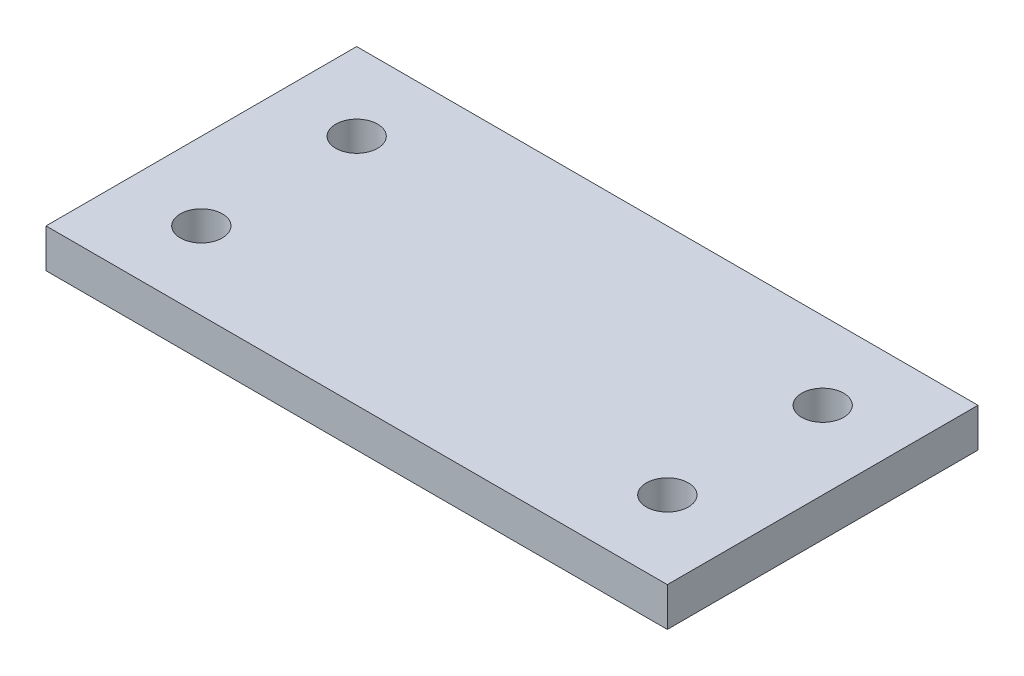
SolidWorks part; units mm, degrees
material "6061 Alloy"
ref_plane "Front Plane" through (0, 0, 0) normal (0, 0, 1) x (1, 0, 0)
ref_plane "Top Plane" through (0, 0, 0) normal (0, 1, 0) x (1, 0, 0)
ref_plane "Right Plane" through (0, 0, 0) normal (1, 0, 0) x (0, 0, -1)
sketch "Sketch1" plane through (0, 0, 0) normal (0, 1, 0) x (1, 0, 0)
  line L1 (-50.8, 25.4) -> (50.8, 25.4)
  line L2 (-50.8, 25.4) -> (-50.8, -25.4)
  line L3 (-50.8, -25.4) -> (50.8, -25.4)
  line L4 (50.8, 25.4) -> (50.8, -25.4)
  line L5 (-50.8, 25.4) -> (50.8, -25.4) construction
  line L6 (-50.8, -25.4) -> (50.8, 25.4) construction
  point P0 (0, 0)
  dimension "D1" = 50.8
  dimension "D2" = 101.6
extrude "Boss-Extrude1" add sketch "Sketch1" along normal blind 6.35
sketch "Sketch3" plane through (0, 0, 0) normal (0, -1, 0) x (1, 0, 0)
  line L0 (0, 0) -> (0, -20.7585) construction
  line L1 (0, 0) -> (-13.1006, 0) construction
  line L2 (-50.8, -25.4) -> (-50.8, 25.4) construction
  line L3 (-50.8, 25.4) -> (50.8, 25.4) construction
  line L4 (50.8, -25.4) -> (-50.8, -25.4) construction
  circle A0 centre (-38.1, 12.7) radius 3.429
  circle A1 centre (-38.1, -12.7) radius 3.429
  circle A2 centre (38.1, 12.7) radius 3.429
  circle A3 centre (38.1, -12.7) radius 3.429
  dimension "D1" = 12.7
  dimension "D2" = 12.7
  dimension "D3" = 12.7
extrude "Cut-Extrude2" cut sketch "Sketch3" against normal up to next
